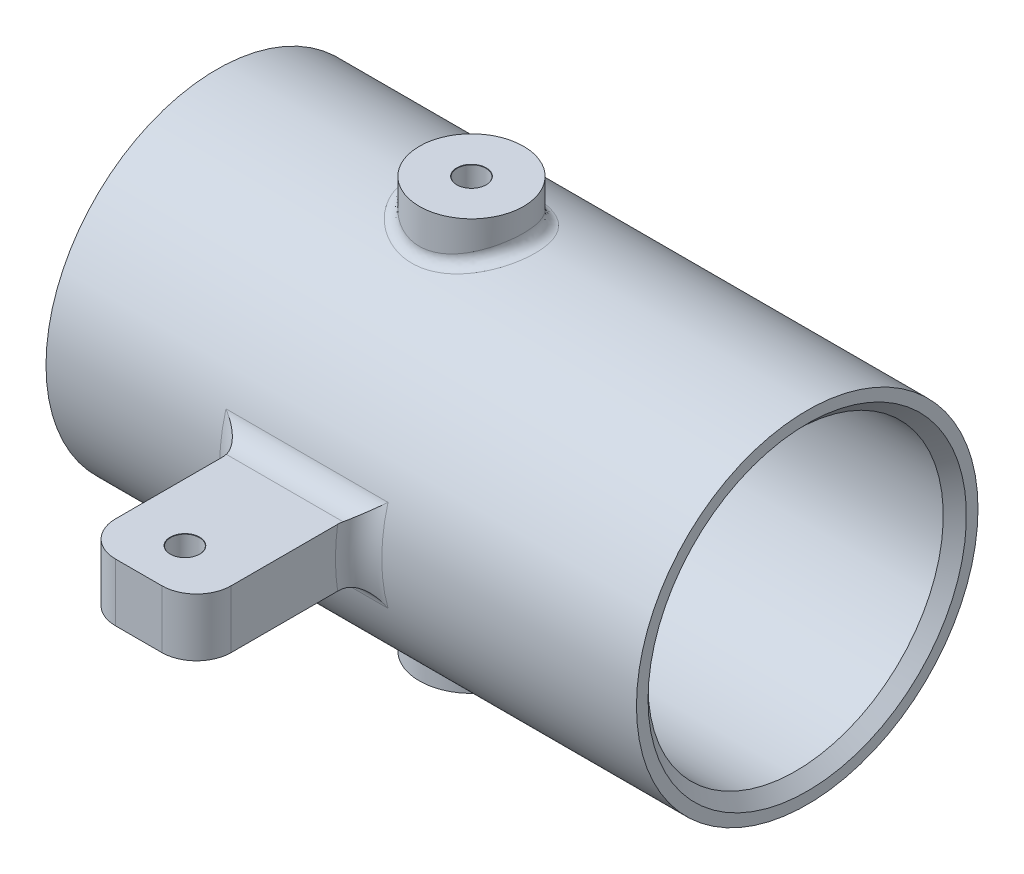
SolidWorks part; units mm, degrees
ref_plane "Front Plane" through (0, 0, 0) normal (0, 0, 1) x (1, 0, 0)
ref_plane "Top Plane" through (0, 0, 0) normal (0, 1, 0) x (1, 0, 0)
ref_plane "Right Plane" through (0, 0, 0) normal (1, 0, 0) x (0, 0, -1)
sketch "Sketch1" plane through (0, 0, 0) normal (0, 0, 1) x (1, 0, 0)
  line L0 (-25.375, 0) -> (51.0417, 0) construction
  line L1 (0, 3.75) -> (0, 14.75)
  line L2 (0, 14.75) -> (51, 14.75)
  line L3 (51, 14.75) -> (51, 12.75)
  line L4 (51, 12.75) -> (2, 12.75)
  line L5 (2, 12.75) -> (2, 3.75)
  line L6 (2, 3.75) -> (0, 3.75)
  dimension "D1" = 7.5
  dimension "D2" = 25.5
  dimension "D3" = 2
  dimension "D4" = 49
  dimension "D5" = 2
revolve "Revolve1" add sketch "Sketch1" angle 360 about L0
sketch "Sketch2" plane through (0, 0, 0) normal (-1, 0, 0) x (0, 0, 1)
  line L0 (0, 13.0742) -> (0, -9.913) construction
  point P0 (-8.5, 0)
  point P1 (8.5, 0)
  dimension "D1" = 17
hole_wizard "M3 Clearance Hole1" positions "Sketch3" profile "Sketch4" hole size "M3" standard "ANSI Metric" end condition up to next
sketch "Sketch3" plane through (0, 0, 0) normal (-1, 0, 0) x (0, 0, 1)
  point P0 (-8.5, 0)
  point P3 (8.5, 0)
sketch "Sketch4" plane through (0, 0, -8.5) normal (0, 1, 0) x (0, 0, 1)
  line L0 (0, 0) -> (0, 2)
  line L1 (0, 2) -> (1.825, 2)
  line L2 (1.8, 1.975) -> (1.8, 0.025)
  line L3 (1.8, 0.025) -> (1.825, 0)
  line L5 (1.825, 0) -> (0, 0)
  line L6 (-1.8, 0.025) -> (-1.825, 0) construction
  line L7 (1.825, 2) -> (1.8, 1.975)
  line L8 (-1.825, 2) -> (-1.8, 1.975) construction
  line L11 (0, -6.35) -> (0, 107.95) construction
  dimension "Thru Hole Dia." = 3.6
  dimension "Thru Hole Depth" = 2
  dimension "Near C'Sink Dia." = 3.65
  dimension "Near C'Sink Angle" = 90
  dimension "Far C'Sink Dia." = 3.65
  dimension "Far C'Sink Angle" = 90
ref_plane "Plane1" through (0, 14.75, 0) normal (0, 1, 0) x (1, 0, 0)
sketch "Sketch5" plane through (0, 14.75, 0) normal (0, 1, 0) x (1, 0, 0)
  line L0 (0, 14.75) -> (0, -14.75) construction
  circle A0 centre (22, 0) radius 4.5
  circle A1 centre (22, 0) radius 2.5 construction
  dimension "D1" = 5
  dimension "D2" = 2
  dimension "D3" = 22
extrude "Boss-Extrude2" add sketch "Sketch5" along normal blind 3 and the other way up to surface
sketch "Sketch6" plane through (0, 17.75, 0) normal (0, 1, 0) x (1, 0, 0)
  circle A0 centre (22, 0) radius 1
  circle A1 centre (22, 0) radius 4.5 construction
  dimension "D1" = 2
extrude "Cut-Extrude1" cut sketch "Sketch6" against normal through all
mirror "Mirror1" about plane through (0, 0, 0) normal (0, 1, 0) of "Cut-Extrude1", "Boss-Extrude2"
fillet "Fillet1" radius 1 2 edges at (22.81, -14.0701, 4.4265) (22.81, 14.0701, 4.4265)
sketch "Sketch7" plane through (0, 0, 0) normal (0, 1, 0) x (1, 0, 0)
  line L0 (22, 26.4042) -> (22, -27.5056) construction
  line L1 (17, -14.75) -> (17, -25.75)
  line L2 (20, -28.75) -> (24, -28.75)
  line L3 (27, -25.75) -> (27, -14.75)
  line L4 (27, -14.75) -> (17, -14.75)
  line L5 (0, 14.75) -> (51, 14.75)
  line L6 (51, -14.75) -> (0, -14.75)
  line L7 (51, -14.75) -> (0, -14.75) construction
  line L8 (0, 14.75) -> (51, 14.75) construction
  circle A0 centre (22, 0) radius 1 construction
  circle A1 centre (22, 0) radius 1 construction
  circle A2 centre (22, -24.75) radius 1
  arc A3 (17, -25.75) -> (20, -28.75) centre (20, -25.75) ccw
  arc A4 (27, -25.75) -> (24, -28.75) centre (24, -25.75) cw
  dimension "2" = 2
  dimension "D2" = 3
  dimension "D3" = 10
  dimension "D4" = 10
  dimension "D5" = 4
extrude "Boss-Extrude3" add sketch "Sketch7" along normal mid plane 5 separate body
sketch "Sketch8" plane through (0, 0, 14.75) normal (0, 0, -1) x (-1, 0, 0)
  line L4 (-27, -2.5) -> (-17, -2.5)
  line L5 (-17, -2.5) -> (-17, 2.5)
  line L6 (-17, 2.5) -> (-27, 2.5)
  line L7 (-27, 2.5) -> (-27, -2.5)
  line L8 (-27, -2.5) -> (-17, -2.5)
  line L9 (-17, -2.5) -> (-17, 2.5)
  line L10 (-17, 2.5) -> (-27, 2.5)
  line L11 (-27, 2.5) -> (-27, -2.5)
  dimension "D1" = 0
extrude "Boss-Extrude4" add sketch "Sketch8" along normal up to surface (0.2134 mm away)
hole_wizard "Tap Drill for M3x0.5 Tap2" positions "Sketch10" profile "Sketch11" hole size "M3x0.5" standard "ANSI Metric" end condition through all
sketch "Sketch10" plane through (0, 17.75, 0) normal (0, 1, 0) x (1, 0, 0)
  point P0 (22, 0)
sketch "Sketch11" plane through (22, 17.75, 0) normal (1, 0, 0) x (0, 0, 1)
  line L0 (0, 0) -> (0, 35.5)
  line L1 (0, 35.5) -> (1.275, 35.5)
  line L2 (1.25, 35.475) -> (1.25, 0.025)
  line L3 (1.25, 0.025) -> (1.275, 0)
  line L5 (1.275, 0) -> (0, 0)
  line L6 (-1.25, 0.025) -> (-1.275, 0) construction
  line L7 (1.275, 35.5) -> (1.25, 35.475)
  line L8 (-1.275, 35.5) -> (-1.25, 35.475) construction
  line L11 (0, -6.35) -> (0, 107.95) construction
  dimension "Thru Hole Dia." = 2.5
  dimension "Thru Hole Depth" = 35.5
  dimension "Near C'Sink Dia." = 2.55
  dimension "Near C'Sink Angle" = 90
  dimension "Far C'Sink Dia." = 2.55
  dimension "Far C'Sink Angle" = 90
hole_wizard "Tap Drill for M3x0.5 Tap1" positions "Sketch12" profile "Sketch13" hole size "M3x0.5" standard "ANSI Metric" end condition through all
sketch "Sketch12" plane through (0, 2.5, 0) normal (0, 1, 0) x (1, 0, 0)
  point P0 (22, -24.75)
sketch "Sketch13" plane through (22, 2.5, 24.75) normal (1, 0, 0) x (0, 0, 1)
  line L0 (0, 0) -> (0, 20.25)
  line L1 (0, 20.25) -> (1.275, 20.25)
  line L2 (1.25, 20.225) -> (1.25, 0.025)
  line L3 (1.25, 0.025) -> (1.275, 0)
  line L5 (1.275, 0) -> (0, 0)
  line L6 (-1.25, 0.025) -> (-1.275, 0) construction
  line L7 (1.275, 20.25) -> (1.25, 20.225)
  line L8 (-1.275, 20.25) -> (-1.25, 20.225) construction
  line L11 (0, -6.35) -> (0, 107.95) construction
  dimension "Thru Hole Dia." = 2.5
  dimension "Thru Hole Depth" = 20.25
  dimension "Near C'Sink Dia." = 2.55
  dimension "Near C'Sink Angle" = 90
  dimension "Far C'Sink Dia." = 2.55
  dimension "Far C'Sink Angle" = 90
chamfer "Chamfer1" distance 1 angle 45 1 edges at (51, 0, 12.75)
chamfer "Chamfer2" distance 0.5 angle 45 2 edges at (0, 0, 3.75) (2, 0, 3.75)
fillet "Fillet2" radius 2 4 edges at (22, -2.5, 14.5366) (27, 0, 14.75) (22, 2.5, 14.5366) (17, 0, 14.75)
